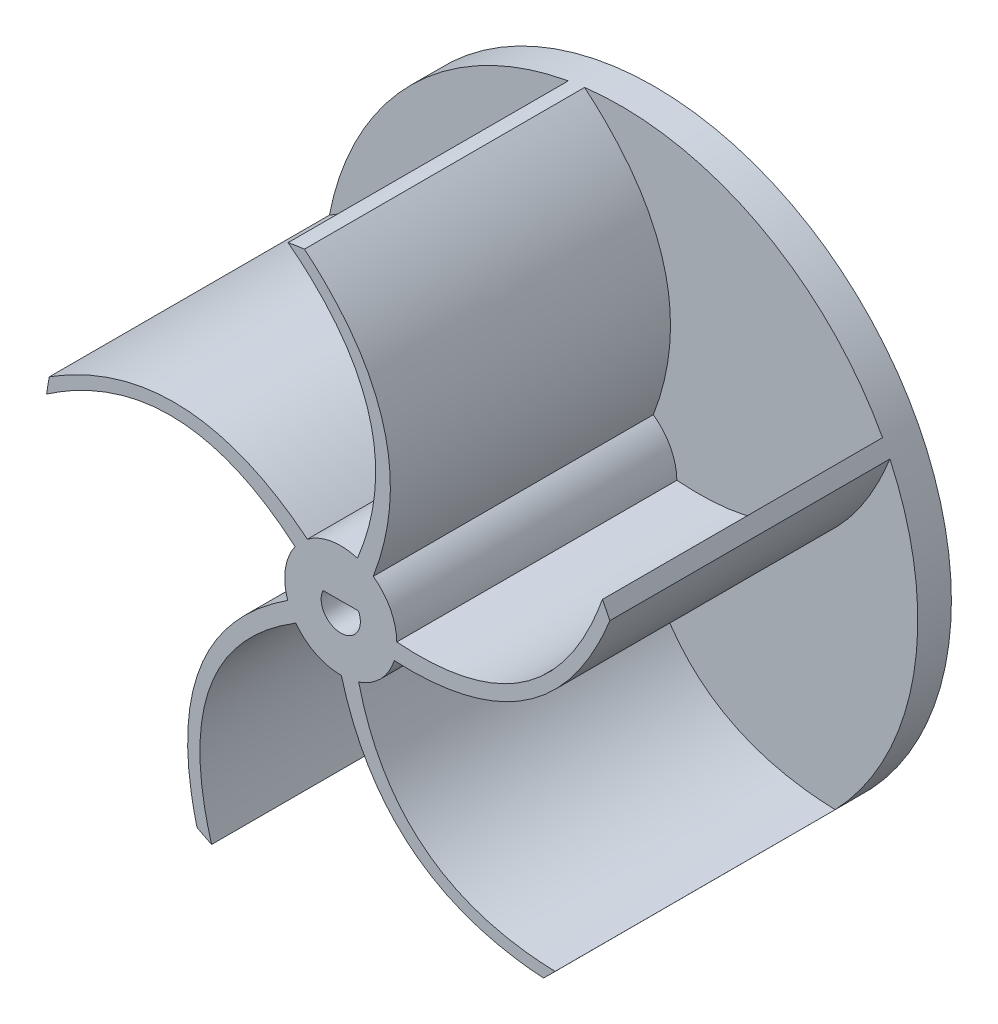
SolidWorks part; units mm, degrees
ref_plane "Front Plane" through (0, 0, 0) normal (0, 0, 1) x (1, 0, 0)
ref_plane "Top Plane" through (0, 0, 0) normal (0, 1, 0) x (1, 0, 0)
ref_plane "Right Plane" through (0, 0, 0) normal (1, 0, 0) x (0, 0, -1)
sketch "Sketch1" plane through (0, 0, 0) normal (0, 0, 1) x (1, 0, 0)
  circle A0 centre (0, 0) radius 26.5
  circle A1 centre (0, 0) radius 1.75
extrude "Boss-Extrude1" add sketch "Sketch1" along normal blind 3
sketch "Sketch2" plane through (0, 0, 3) normal (0, 0, 1) x (1, 0, 0)
  line L0 (0, 1.75) -> (0, 0.75) construction
  line L1 (-1.5811, 0.75) -> (1.5811, 0.75)
  line L2 (0, 0.75) -> (-1.5811, 0.75)
  circle A0 centre (0, 0) radius 5
  circle A1 centre (0, 0) radius 1.75
extrude "Boss-Extrude2" add sketch "Sketch2" along normal blind 25 contours A0 L2
sketch "Sketch3" plane through (0, 0, 28) normal (0, 0, 1) x (1, 0, 0)
  line L0 (-1.5811, 0.75) -> (1.5811, 0.75) construction
  line L1 (0, 0.75) -> (-1.5811, 0.75) construction
  line L2 (-1.5811, 0.75) -> (1.5811, 0.75)
  line L3 (0, 0.75) -> (-1.5811, 0.75)
  circle A1 centre (0, 0) radius 1.75
  arc A2 (1.5811, 0.75) -> (-1.5811, 0.75) centre (0, 0) ccw
  circle M3 centre (0, 0) radius 1.75
  dimension "D1" = 0
extrude "Boss-Extrude3" add sketch "Sketch3" against normal blind 28 contours L2 M3
sketch "Sketch4" plane through (0, 0, 3) normal (0, 0, 1) x (1, 0, 0)
  line L0 (0, 0) -> (0, 26.5) construction
  line L1 (0, 0) -> (-1, 0) construction
  line L2 (-1, 0) -> (1, 0) construction
  circle A0 centre (0, 0) radius 26.5 construction
  arc A2 (2.8968, 4.0754) -> (1.4915, 4.7724) centre (0, 0) ccw
  arc A3 (-3.2413, 26.301) -> (-4.6974, 26.0804) centre (0, 0) ccw
  spline S0 degree 2 poles (-1, 0) (-0.4653, 0.8562) (0, 1.6968) knots 0 0 0 0.054655 0.054655 0.054655
  spline S1 degree 3 poles (2.8968, 4.0754) (6.2008, 12.7436) (4.1548, 20.1522) (-3.2413, 26.301) knots 0.132925 0.132925 0.132925 0.132925 1 1 1 1
  spline S2 degree 3 poles (1.4915, 4.7724) (4.9474, 13.1209) (2.8844, 20.2235) (-4.6974, 26.0804) knots 0.156415 0.156415 0.156415 0.156415 1 1 1 1
  circle M4 centre (0, 0) radius 5
  circle M5 centre (0, 0) radius 26.5
extrude "Boss-Extrude4" add sketch "Sketch4" along normal blind 25 contours S2 S1 M4 M5
pattern_circular "CirPattern1" count 5 over 360 of "Boss-Extrude4"
